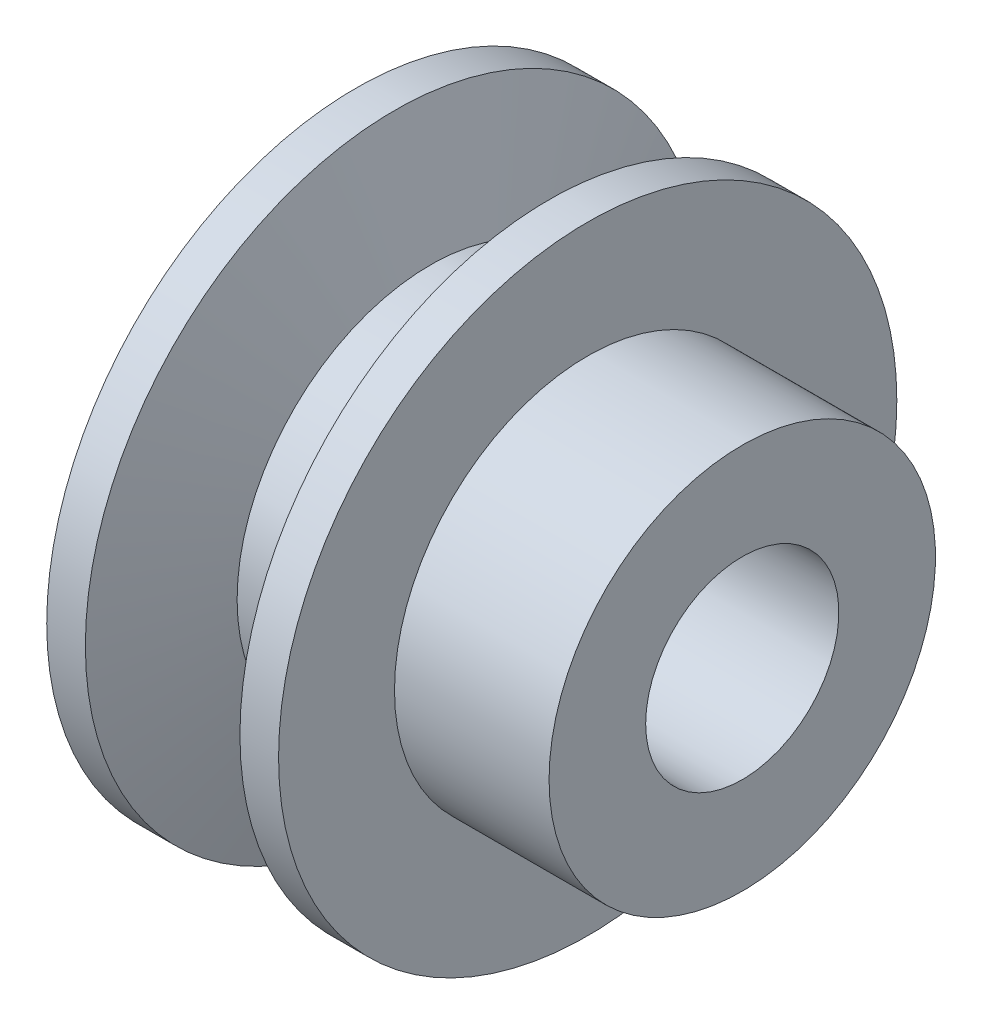
SolidWorks part; units mm, degrees
ref_plane "Front Plane" through (0, 0, 0) normal (0, 0, 1) x (1, 0, 0)
ref_plane "Top Plane" through (0, 0, 0) normal (0, 1, 0) x (1, 0, 0)
ref_plane "Right Plane" through (0, 0, 0) normal (1, 0, 0) x (0, 0, -1)
sketch "Sketch1" plane through (0, 0, 0) normal (0, 0, 1) x (1, 0, 0)
  line L0 (0, 0) -> (1270, 0) construction
  line L1 (635, 1016) -> (474.6259, 635)
  line L2 (1270, 317.5) -> (1270, 635)
  line L3 (1270, 635) -> (762, 635)
  line L4 (762, 635) -> (762, 1016)
  line L5 (762, 1016) -> (635, 1016)
  line L7 (127, 1016) -> (244.7377, 635)
  line L9 (127, 1016) -> (0, 1016)
  line L11 (474.6259, 635) -> (244.7377, 635)
  line L12 (0, 508) -> (0, 1016)
  line L13 (1270, 317.5) -> (190.5, 317.5)
  line L14 (190.5, 317.5) -> (0, 508)
  dimension "D1" = 127
  dimension "D2" = 190.5
  dimension "D3" = 508
  dimension "D4" = 317.5
  dimension "D5" = 508
  dimension "D6" = 508
  dimension "D7" = 40
  dimension "D9" = 229.8882
revolve "Revolve1" add sketch "Sketch1" angle 360 about L0
